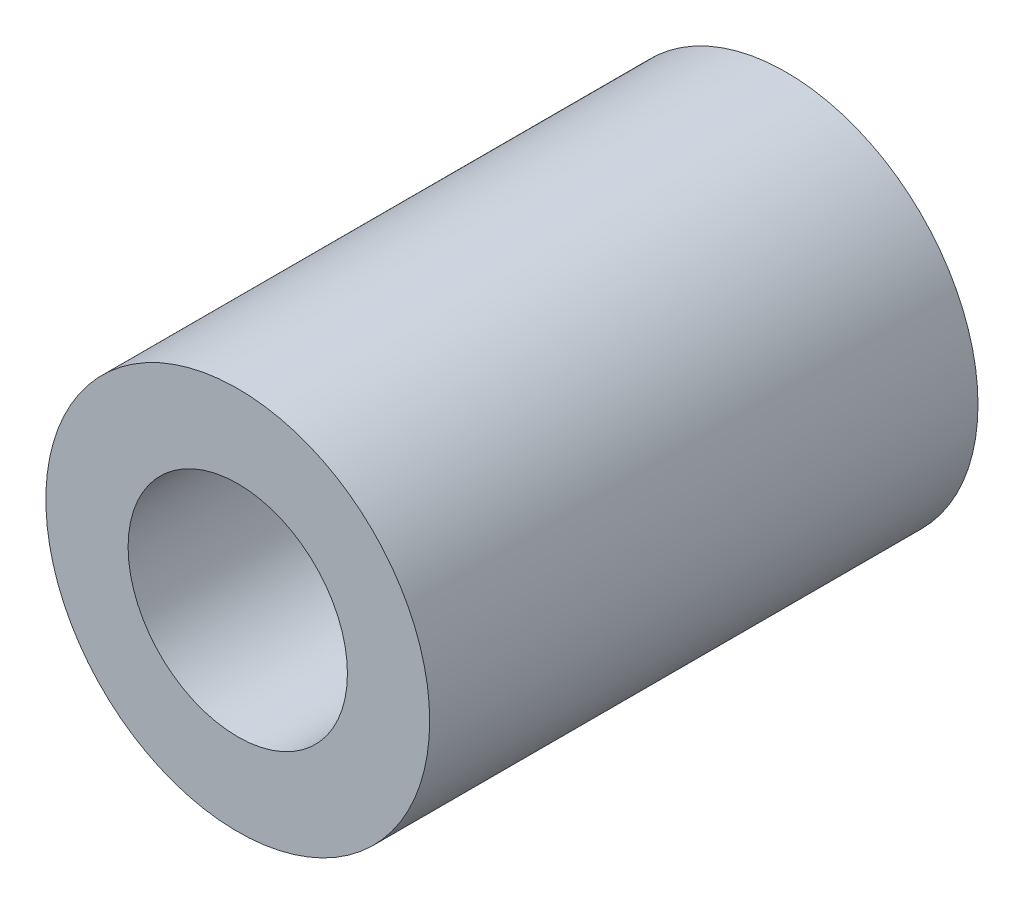
SolidWorks part; units mm, degrees
ref_plane "정면" through (0, 0, 0) normal (0, 0, 1) x (1, 0, 0)
ref_plane "윗면" through (0, 0, 0) normal (0, 1, 0) x (1, 0, 0)
ref_plane "우측면" through (0, 0, 0) normal (1, 0, 0) x (0, 0, -1)
sketch "스케치1" plane through (0, 0, 0) normal (0, 0, 1) x (1, 0, 0)
  circle A0 centre (0, 0) radius 3.5
  circle A1 centre (0, 0) radius 2
  dimension "D1" = 4
  dimension "D2" = 7
extrude "보스-돌출1" add sketch "스케치1" along normal blind 10
